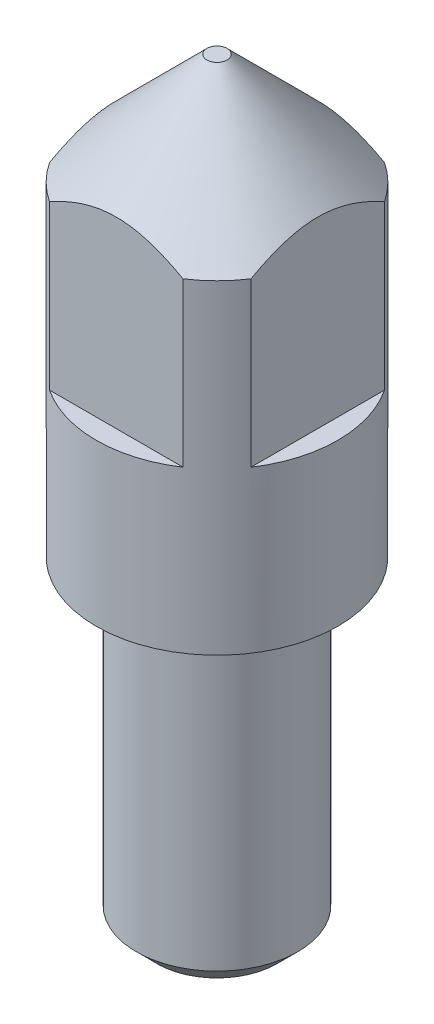
SolidWorks part; units mm, degrees
material "SUS304"
ref_plane "Front" through (0, 0, 0) normal (0, 0, 1) x (1, 0, 0)
ref_plane "Top" through (0, 0, 0) normal (0, 1, 0) x (1, 0, 0)
ref_plane "Right" through (0, 0, 0) normal (1, 0, 0) x (0, 0, -1)
sketch "Sketch1" plane through (0, 0, 0) normal (0, 0, 1) x (1, 0, 0)
  line L0 (0, -10.5932) -> (0, 18.3476) construction
  line L1 (0, -8) -> (2, -8)
  line L2 (2, -8) -> (2, 0)
  line L3 (2, 0) -> (3, 0)
  line L4 (3, 0) -> (3, 10.8)
  line L5 (3, 10.8) -> (0, 10.8)
  line L6 (0, 10.8) -> (0, -8)
  dimension "D1" = 4
  dimension "D2" = 6
  dimension "D3" = 8
  dimension "D4" = 18.8
revolve "Revolve1" add sketch "Sketch1" angle 360 about L0
cosmetic thread "Cosmetic Thread1" parameters "D1"=5, "D2"=3.22
chamfer "Chamfer1" distance 2.75 angle 45 1 edges at (0, 10.8, -3)
sketch "Sketch2" plane through (0, 10.8, 0) normal (0, 1, 0) x (1, 0, 0)
  line L0 (-3.4357, 0) -> (3.452, 0) construction
  line L1 (-2.5, 2.5) -> (2.5, 2.5)
  line L2 (-2.5, 2.5) -> (-2.5, -2.5)
  line L3 (-2.5, -2.5) -> (2.5, -2.5)
  line L4 (2.5, 2.5) -> (2.5, -2.5)
  line L5 (0, 3.3347) -> (0, -3.2739) construction
  dimension "D1" = 5
extrude "Cut-Extrude1" cut sketch "Sketch2" against normal blind 6.8 flip side to cut
chamfer "Chamfer2" distance 0.5 angle 45 1 edges at (0, -8, -2)
